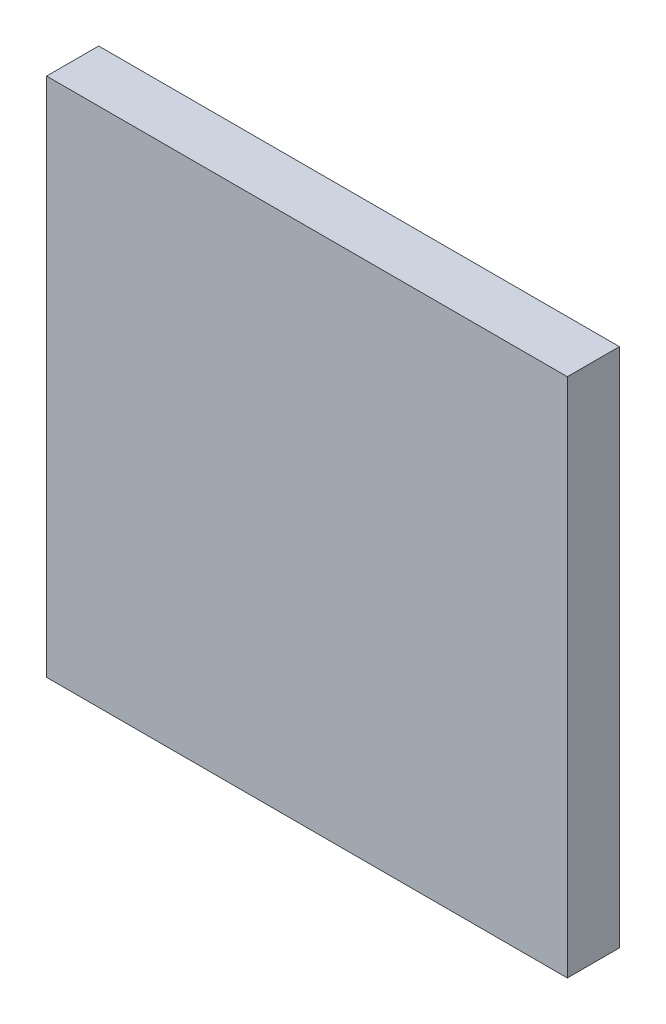
SolidWorks part; units mm, degrees
material "Mahogany"
ref_plane "Front" through (0, 0, 0) normal (0, 0, 1) x (1, 0, 0)
ref_plane "Top" through (0, 0, 0) normal (0, 1, 0) x (1, 0, 0)
ref_plane "Right" through (0, 0, 0) normal (1, 0, 0) x (0, 0, -1)
sketch "Sketch2" plane through (0, 0, 0) normal (0, 0, 1) x (1, 0, 0)
  line L1 (-50, 100) -> (50, 100)
  line L2 (-50, 100) -> (-50, 0)
  line L3 (-50, 0) -> (50, 0)
  line L4 (50, 100) -> (50, 0)
  line L5 (-50, 100) -> (50, 0) construction
  line L6 (-50, 0) -> (50, 100) construction
  point P4 (0, 50)
  dimension "D1" = 100
  dimension "D2" = 100
extrude "Boss-Extrude1" add sketch "Sketch2" along normal blind 10
sketch "Sketch3" plane through (0, 0, 0) normal (0, 0, -1) x (-1, 0, 0)
  line L0 (-50, 100) -> (50, 100) construction
  line L1 (-43.0962, 95) -> (45, 95)
  line L2 (-43.0962, 95) -> (-43.0962, 5)
  line L3 (-43.0962, 5) -> (45, 5)
  line L4 (45, 95) -> (45, 5)
  line L7 (50, 0) -> (-50, 0) construction
  line L8 (50, 100) -> (50, 0) construction
  point P4 (0.9519, 50)
  dimension "D1" = 90
  dimension "D2" = 5
  dimension "D3" = 5
  dimension "D4" = 5
  dimension "D5" = 100
extrude "Cut-Extrude1" cut sketch "Sketch3" against normal blind 5
